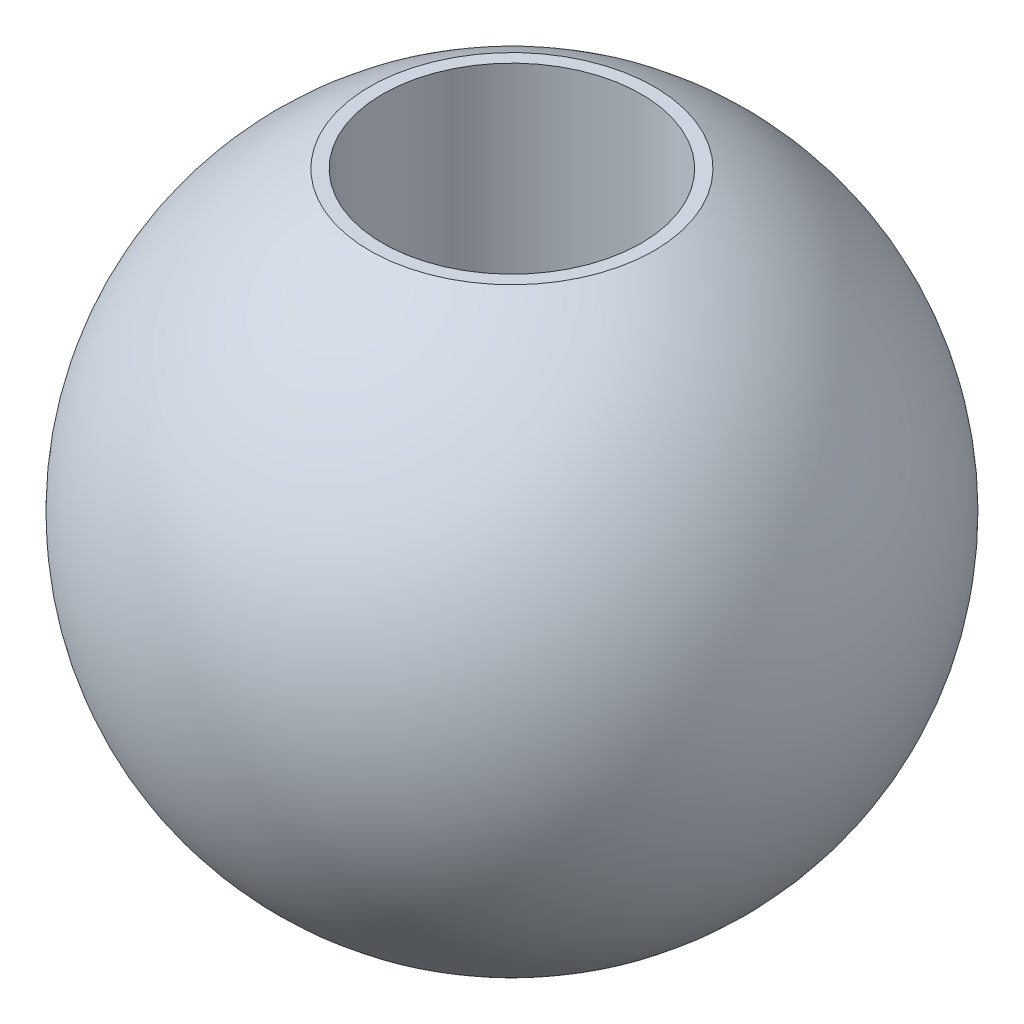
SolidWorks part; units mm, degrees
material "Brass"
ref_plane "Front Plane" through (0, 0, 0) normal (0, 0, 1) x (1, 0, 0)
ref_plane "Top Plane" through (0, 0, 0) normal (0, 1, 0) x (1, 0, 0)
ref_plane "Right Plane" through (0, 0, 0) normal (1, 0, 0) x (0, 0, -1)
sketch "Sketch1" plane through (0, 0, 0) normal (0, 0, 1) x (1, 0, 0)
  line L0 (0, -1000) -> (0, 49000) construction
  line L1 (0, 0) -> (0, 2.3) construction
  line L2 (0, 0) -> (0, -2.3) construction
  line L3 (0, 2.3) -> (1.1, 2.3) construction
  line L5 (1.1, 2.3) -> (1, 2.3)
  line L6 (1, 2.3) -> (1, -2.3)
  line L7 (1, -2.3) -> (1.1, -2.3)
  line L8 (-2.5495, 0) -> (2.5495, 0) construction
  arc A0 (1.1, 2.3) -> (1.1, -2.3) centre (0, 0) cw
  point P12 (0, 0)
  point P14 (2.5495, 0)
  dimension "D4" = 0.1
  dimension "D1" = 4.6
  dimension "D2" = 2.3
  dimension "D3" = 1
  dimension "D5" = 5.099
revolve "Revolve1" add sketch "Sketch1" angle 360 about L0
ref_point "Point1"
